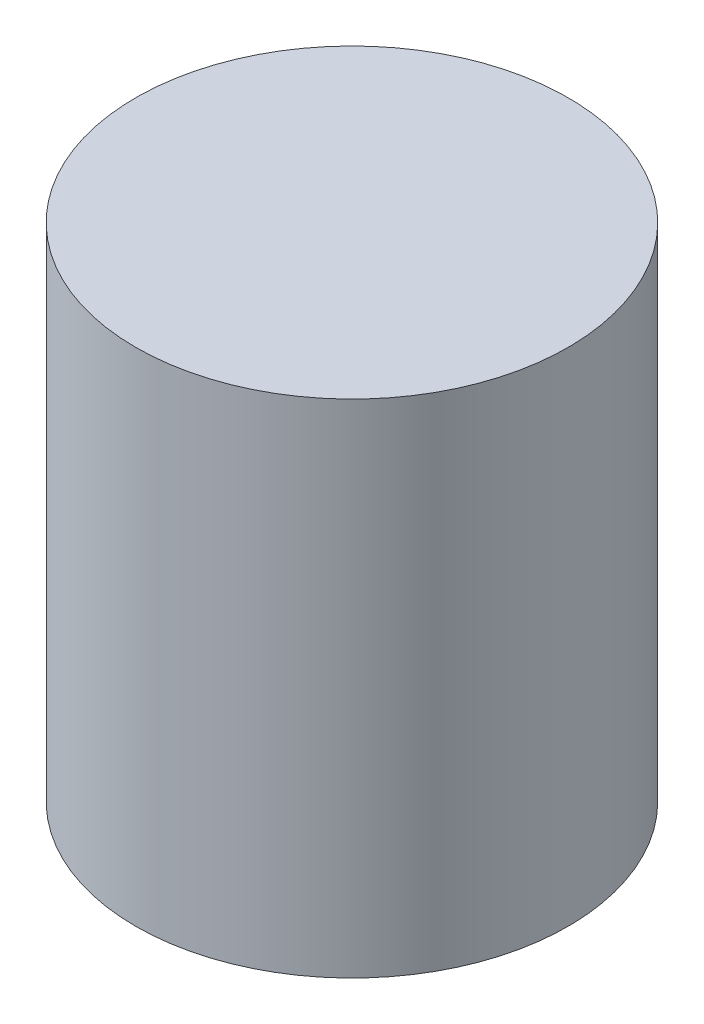
SolidWorks part; units mm, degrees
ref_plane "Front Plane" through (0, 0, 0) normal (0, 0, 1) x (1, 0, 0)
ref_plane "Top Plane" through (0, 0, 0) normal (0, 1, 0) x (1, 0, 0)
ref_plane "Right Plane" through (0, 0, 0) normal (1, 0, 0) x (0, 0, -1)
sketch "Sketch1" plane through (0, 0, 0) normal (0, 1, 0) x (1, 0, 0)
  circle A0 centre (0, 0) radius 6.9
  dimension "D1" = 13.8
extrude "Boss-Extrude1" add sketch "Sketch1" along normal blind 16
